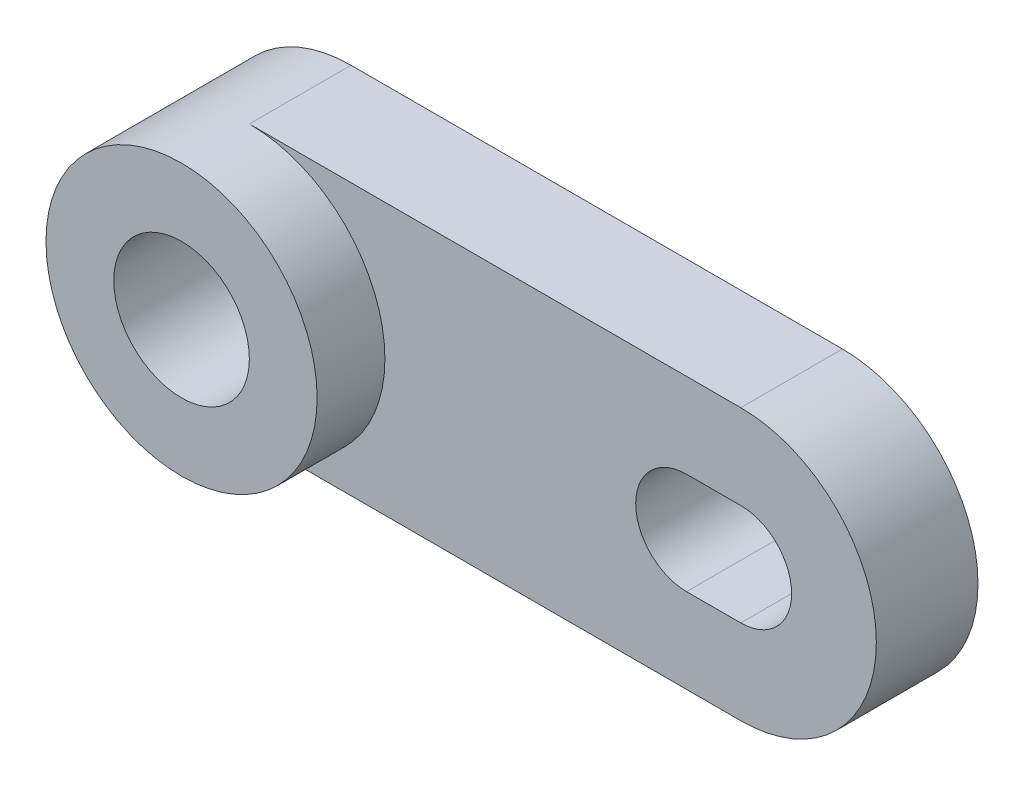
SolidWorks part; units mm, degrees
material "ABS"
ref_plane "Alzado" through (0, 0, 0) normal (0, 0, 1) x (1, 0, 0)
ref_plane "Planta" through (0, 0, 0) normal (0, 1, 0) x (1, 0, 0)
ref_plane "Vista lateral" through (0, 0, 0) normal (1, 0, 0) x (0, 0, -1)
sketch "Croquis1" plane through (0, 0, 0) normal (0, 0, 1) x (1, 0, 0)
  line L0 (0, 4) -> (14.5, 4)
  line L1 (0, -4) -> (14.5, -4)
  line L3 (12.9, -1.5) -> (14.5, -1.5)
  line L4 (12.9, -1.5) -> (12.9, 1.5)
  line L5 (12.9, 1.5) -> (14.5, 1.5)
  line L6 (14.5, -1.5) -> (14.5, 1.5)
  circle A0 centre (0, 0) radius 4
  circle A1 centre (0, 0) radius 2
  circle A2 centre (14.5, 0) radius 1.5
  circle A3 centre (14.5, 0) radius 4
  circle A4 centre (12.9, 0) radius 1.5
  point P17 (0, 0)
  point P18 (0, 0)
  point P19 (13, -4)
  dimension "D1" = 8
  dimension "D2" = 4
  dimension "D3" = 3
  dimension "D4" = 8
  dimension "D6" = 3
  dimension "D5" = 14.5
  dimension "D7" = 12.9
extrude "Saliente-Extruir1" add sketch "Croquis1" along normal blind 3 contours A0 A1 | A3 L0 A0 L1 | A3 A4 L5 A2 L3
sketch "Croquis2" plane through (0, 0, 3) normal (0, 0, 1) x (1, 0, 0)
  circle A0 centre (0, 0) radius 2
  circle A1 centre (0, 0) radius 4
extrude "Saliente-Extruir2" add sketch "Croquis2" along normal blind 2
sketch "Croquis3" plane through (0, 0, 0) normal (0, 0, -1) x (-1, 0, 0)
  circle A0 centre (0, 0) radius 2.5
  dimension "D1" = 5
extrude "Cortar-Extruir1" cut sketch "Croquis3" against normal blind 2
